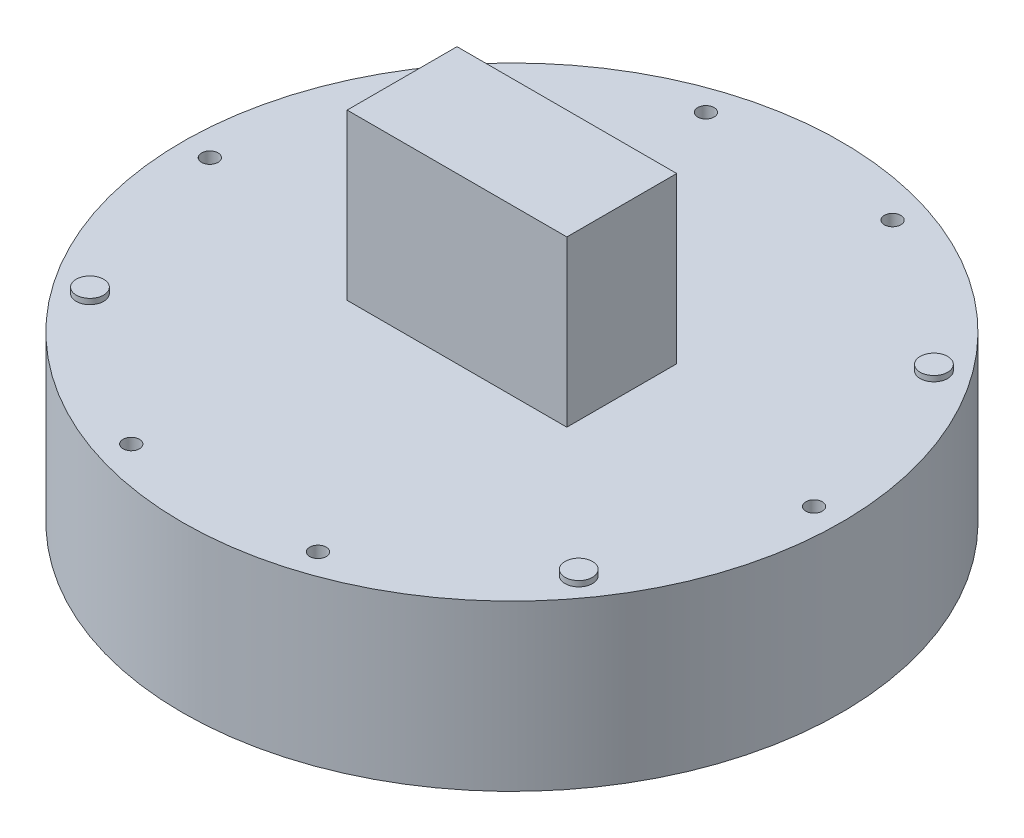
SolidWorks part; units mm, degrees
ref_plane "前视基准面" through (0, 0, 0) normal (0, 0, 1) x (1, 0, 0)
ref_plane "上视基准面" through (0, 0, 0) normal (0, 1, 0) x (1, 0, 0)
ref_plane "右视基准面" through (0, 0, 0) normal (1, 0, 0) x (0, 0, -1)
sketch "草图1" plane through (0, 0, 0) normal (0, 1, 0) x (1, 0, 0)
  circle A0 centre (0, 0) radius 60
  dimension "D1" = 120
extrude "凸台-拉伸1" add sketch "草图1" along normal blind 30
sketch "草图2" plane through (0, 30, 0) normal (0, 1, 0) x (1, 0, 0)
  circle A0 centre (0, 0) radius 55 construction
  circle A1 centre (55, 0) radius 1.5
  dimension "D1" = 110
  dimension "D2" = 3
extrude "切除-拉伸1" cut sketch "草图2" against normal blind 5
pattern_circular "阵列(圆周)1" count 10 over 360 about axis through (0, 0, 0) along (0, 1, 0) of "切除-拉伸1"
sketch "草图3" plane through (0, 30, 0) normal (0, 1, 0) x (1, 0, 0)
  line L1 (-20, 10) -> (20, 10)
  line L2 (-20, 10) -> (-20, -10)
  line L3 (-20, -10) -> (20, -10)
  line L4 (20, 10) -> (20, -10)
  line L5 (-20, 10) -> (20, -10) construction
  line L6 (-20, -10) -> (20, 10) construction
  point P0 (0, 0)
  dimension "D1" = 20
  dimension "D2" = 40
extrude "凸台-拉伸2" add sketch "草图3" along normal blind 30
sketch "草图5" plane through (0, 30, 0) normal (0, 1, 0) x (1, 0, 0)
  circle A0 centre (-44.4959, 32.3282) radius 2.5
  circle A3 centre (44.4959, -32.3282) radius 2.5
  circle A4 centre (44.4959, 32.3282) radius 2.5
  circle A5 centre (-44.4959, -32.3282) radius 2.5
  dimension "D1" = 5
extrude "凸台-拉伸4" add sketch "草图5" along normal blind 1
